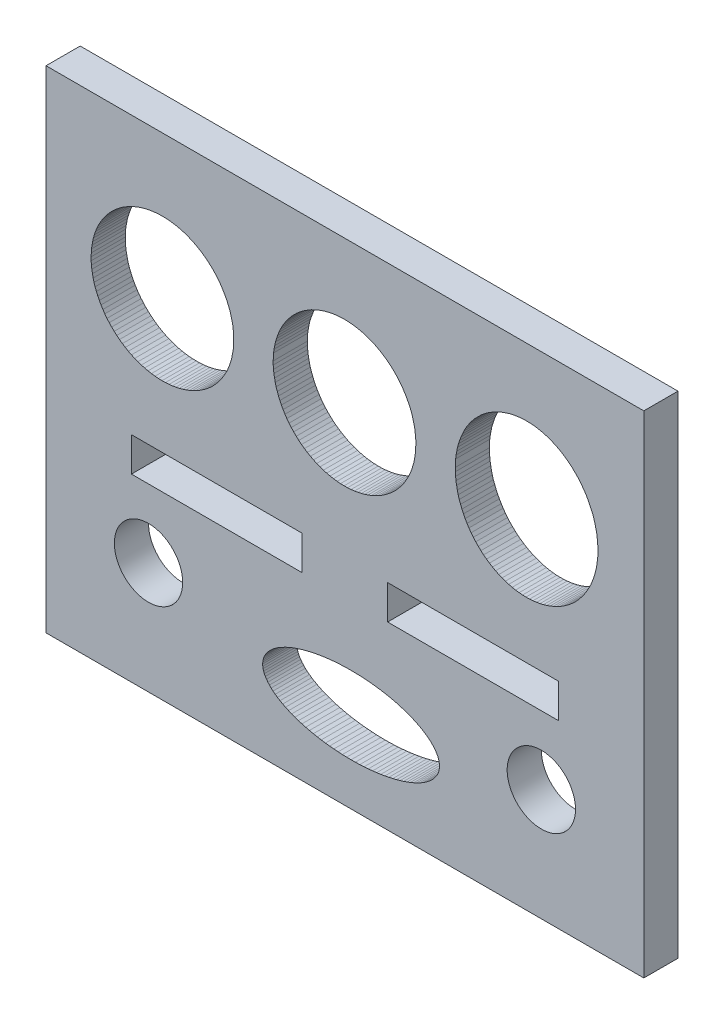
SolidWorks part; units mm, degrees
ref_plane "前视基准面" through (0, 0, 0) normal (0, 0, 1) x (1, 0, 0)
ref_plane "上视基准面" through (0, 0, 0) normal (0, 1, 0) x (1, 0, 0)
ref_plane "右视基准面" through (0, 0, 0) normal (1, 0, 0) x (0, 0, -1)
sketch "Model" plane through (0, 0, 0) normal (0, 0, 1) x (1, 0, 0)
  line L0 (794.7597, 604.4916) -> (759.7597, 604.4916)
  line L1 (789.7597, 617.0426) -> (789.7597, 615.0426)
  line L2 (789.7597, 617.0426) -> (779.7597, 617.0426)
  line L3 (779.7597, 615.0426) -> (779.7597, 617.0426)
  line L4 (774.7597, 617.0426) -> (764.7597, 617.0426)
  line L5 (764.7597, 615.0426) -> (764.7597, 617.0426)
  line L6 (789.7597, 615.0426) -> (779.7597, 615.0426)
  line L7 (774.7597, 615.0426) -> (764.7597, 615.0426)
  line L8 (774.7597, 617.0426) -> (774.7597, 615.0426)
  line L9 (794.7597, 633.2493) -> (759.7597, 633.2493)
  line L10 (759.7597, 633.2493) -> (759.7597, 604.4916)
  line L11 (794.7597, 633.2493) -> (794.7597, 604.4916)
  line L12 (787.8604, 620.3577) -> (788.0704, 620.3607)
  line L13 (788.0704, 620.3607) -> (788.2704, 620.3757)
  line L14 (788.2704, 620.3757) -> (788.4804, 620.4017)
  line L15 (788.4804, 620.4017) -> (788.6804, 620.4377)
  line L16 (788.6804, 620.4377) -> (788.8804, 620.4837)
  line L17 (788.8804, 620.4837) -> (789.0804, 620.5417)
  line L18 (789.0804, 620.5417) -> (789.2704, 620.6087)
  line L19 (789.2704, 620.6087) -> (789.4604, 620.6867)
  line L20 (789.4604, 620.6867) -> (789.6504, 620.7737)
  line L21 (789.6504, 620.7737) -> (789.8404, 620.8717)
  line L22 (789.8404, 620.8717) -> (790.0204, 620.9787)
  line L23 (790.0204, 620.9787) -> (790.1904, 621.0947)
  line L24 (790.1904, 621.0947) -> (790.3604, 621.2197)
  line L25 (790.3604, 621.2197) -> (790.5204, 621.3537)
  line L26 (790.5204, 621.3537) -> (790.6804, 621.4957)
  line L27 (790.6804, 621.4957) -> (790.8304, 621.6467)
  line L28 (790.8304, 621.6467) -> (790.9704, 621.8047)
  line L29 (790.9704, 621.8047) -> (791.1004, 621.9697)
  line L30 (791.1004, 621.9697) -> (791.2304, 622.1417)
  line L31 (791.2304, 622.1417) -> (791.3504, 622.3207)
  line L32 (791.3504, 622.3207) -> (791.4604, 622.5057)
  line L33 (791.4604, 622.5057) -> (791.5604, 622.6957)
  line L34 (791.5604, 622.6957) -> (791.6604, 622.8917)
  line L35 (791.6604, 622.8917) -> (791.7404, 623.0917)
  line L36 (791.7404, 623.0917) -> (791.8204, 623.2957)
  line L37 (791.8204, 623.2957) -> (791.8804, 623.5037)
  line L38 (791.8804, 623.5037) -> (791.9404, 623.7147)
  line L39 (791.9404, 623.7147) -> (791.9904, 623.9287)
  line L40 (791.9904, 623.9287) -> (792.0204, 624.1447)
  line L41 (792.0204, 624.1447) -> (792.0504, 624.3627)
  line L42 (792.0504, 624.3627) -> (792.0704, 624.5817)
  line L43 (792.0704, 624.5817) -> (792.0704, 624.8017)
  line L44 (792.0704, 624.8017) -> (792.0704, 625.0207)
  line L45 (792.0704, 625.0207) -> (792.0504, 625.2397)
  line L46 (792.0504, 625.2397) -> (792.0304, 625.4577)
  line L47 (792.0304, 625.4577) -> (792.0004, 625.6747)
  line L48 (792.0004, 625.6747) -> (791.9504, 625.8887)
  line L49 (791.9504, 625.8887) -> (791.9004, 626.1007)
  line L50 (791.9004, 626.1007) -> (791.8404, 626.3097)
  line L51 (791.8404, 626.3097) -> (791.7704, 626.5157)
  line L52 (791.7704, 626.5157) -> (791.6804, 626.7167)
  line L53 (791.6804, 626.7167) -> (791.5904, 626.9137)
  line L54 (791.5904, 626.9137) -> (791.4904, 627.1057)
  line L55 (791.4904, 627.1057) -> (791.3904, 627.2917)
  line L56 (791.3904, 627.2917) -> (791.2704, 627.4717)
  line L57 (791.2704, 627.4717) -> (791.1404, 627.6457)
  line L58 (791.1404, 627.6457) -> (791.0104, 627.8137)
  line L59 (791.0104, 627.8137) -> (790.8704, 627.9737)
  line L60 (790.8704, 627.9737) -> (790.7204, 628.1257)
  line L61 (790.7204, 628.1257) -> (790.5704, 628.2707)
  line L62 (790.5704, 628.2707) -> (790.4104, 628.4067)
  line L63 (790.4104, 628.4067) -> (790.2404, 628.5347)
  line L64 (790.2404, 628.5347) -> (790.0704, 628.6527)
  line L65 (790.0704, 628.6527) -> (789.8904, 628.7627)
  line L66 (789.8904, 628.7627) -> (789.7104, 628.8627)
  line L67 (789.7104, 628.8627) -> (789.5204, 628.9527)
  line L68 (789.5204, 628.9527) -> (789.3304, 629.0327)
  line L69 (789.3304, 629.0327) -> (789.1404, 629.1037)
  line L70 (789.1404, 629.1037) -> (788.9404, 629.1637)
  line L71 (788.9404, 629.1637) -> (788.7404, 629.2127)
  line L72 (788.7404, 629.2127) -> (788.5404, 629.2517)
  line L73 (788.5404, 629.2517) -> (788.3404, 629.2807)
  line L74 (788.3404, 629.2807) -> (788.1304, 629.2977)
  line L75 (788.1304, 629.2977) -> (787.9304, 629.3047)
  line L76 (787.9304, 629.3047) -> (787.7204, 629.3007)
  line L77 (787.7204, 629.3007) -> (787.5204, 629.2857)
  line L78 (787.5204, 629.2857) -> (787.3204, 629.2607)
  line L79 (787.3204, 629.2607) -> (787.1104, 629.2247)
  line L80 (787.1104, 629.2247) -> (786.9104, 629.1777)
  line L81 (786.9104, 629.1777) -> (786.7204, 629.1207)
  line L82 (786.7204, 629.1207) -> (786.5204, 629.0537)
  line L83 (786.5204, 629.0537) -> (786.3304, 628.9757)
  line L84 (786.3304, 628.9757) -> (786.1404, 628.8877)
  line L85 (786.1404, 628.8877) -> (785.9604, 628.7907)
  line L86 (785.9604, 628.7907) -> (785.7804, 628.6837)
  line L87 (785.7804, 628.6837) -> (785.6004, 628.5677)
  line L88 (785.6004, 628.5677) -> (785.4404, 628.4417)
  line L89 (785.4404, 628.4417) -> (785.2704, 628.3077)
  line L90 (785.2704, 628.3077) -> (785.1204, 628.1657)
  line L91 (785.1204, 628.1657) -> (784.9704, 628.0157)
  line L92 (784.9704, 628.0157) -> (784.8204, 627.8577)
  line L93 (784.8204, 627.8577) -> (784.6904, 627.6917)
  line L94 (784.6904, 627.6917) -> (784.5604, 627.5197)
  line L95 (784.5604, 627.5197) -> (784.4404, 627.3407)
  line L96 (784.4404, 627.3407) -> (784.3304, 627.1567)
  line L97 (784.3304, 627.1567) -> (784.2304, 626.9657)
  line L98 (784.2304, 626.9657) -> (784.1404, 626.7707)
  line L99 (784.1404, 626.7707) -> (784.0504, 626.5707)
  line L100 (784.0504, 626.5707) -> (783.9804, 626.3657)
  line L101 (783.9804, 626.3657) -> (783.9104, 626.1577)
  line L102 (783.9104, 626.1577) -> (783.8504, 625.9467)
  line L103 (783.8504, 625.9467) -> (783.8104, 625.7327)
  line L104 (783.8104, 625.7327) -> (783.7704, 625.5167)
  line L105 (783.7704, 625.5167) -> (783.7404, 625.2987)
  line L106 (783.7404, 625.2987) -> (783.7304, 625.0797)
  line L107 (783.7304, 625.0797) -> (783.7204, 624.8607)
  line L108 (783.7204, 624.8607) -> (783.7204, 624.6407)
  line L109 (783.7204, 624.6407) -> (783.7404, 624.4217)
  line L110 (783.7404, 624.4217) -> (783.7604, 624.2037)
  line L111 (783.7604, 624.2037) -> (783.8004, 623.9877)
  line L112 (783.8004, 623.9877) -> (783.8404, 623.7727)
  line L113 (783.8404, 623.7727) -> (783.8904, 623.5607)
  line L114 (783.8904, 623.5607) -> (783.9504, 623.3517)
  line L115 (783.9504, 623.3517) -> (784.0304, 623.1467)
  line L116 (784.0304, 623.1467) -> (784.1104, 622.9447)
  line L117 (784.1104, 622.9447) -> (784.2004, 622.7487)
  line L118 (784.2004, 622.7487) -> (784.3004, 622.5567)
  line L119 (784.3004, 622.5567) -> (784.4104, 622.3707)
  line L120 (784.4104, 622.3707) -> (784.5204, 622.1897)
  line L121 (784.5204, 622.1897) -> (784.6504, 622.0157)
  line L122 (784.6504, 622.0157) -> (784.7804, 621.8487)
  line L123 (784.7804, 621.8487) -> (784.9204, 621.6887)
  line L124 (784.9204, 621.6887) -> (785.0704, 621.5357)
  line L125 (785.0704, 621.5357) -> (785.2204, 621.3917)
  line L126 (785.2204, 621.3917) -> (785.3804, 621.2557)
  line L127 (785.3804, 621.2557) -> (785.5504, 621.1277)
  line L128 (785.5504, 621.1277) -> (785.7204, 621.0087)
  line L129 (785.7204, 621.0087) -> (785.9004, 620.8997)
  line L130 (785.9004, 620.8997) -> (786.0804, 620.7997)
  line L131 (786.0804, 620.7997) -> (786.2704, 620.7087)
  line L132 (786.2704, 620.7087) -> (786.4604, 620.6287)
  line L133 (786.4604, 620.6287) -> (786.6504, 620.5587)
  line L134 (786.6504, 620.5587) -> (786.8504, 620.4987)
  line L135 (786.8504, 620.4987) -> (787.0504, 620.4487)
  line L136 (787.0504, 620.4487) -> (787.2504, 620.4097)
  line L137 (787.2504, 620.4097) -> (787.4604, 620.3817)
  line L138 (787.4604, 620.3817) -> (787.6604, 620.3637)
  line L139 (787.6604, 620.3637) -> (787.8604, 620.3577)
  line L140 (777.2104, 620.6747) -> (777.4104, 620.6777)
  line L141 (777.4104, 620.6777) -> (777.6204, 620.6917)
  line L142 (777.6204, 620.6917) -> (777.8204, 620.7157)
  line L143 (777.8204, 620.7157) -> (778.0204, 620.7497)
  line L144 (778.0204, 620.7497) -> (778.2204, 620.7937)
  line L145 (778.2204, 620.7937) -> (778.4204, 620.8477)
  line L146 (778.4204, 620.8477) -> (778.6104, 620.9117)
  line L147 (778.6104, 620.9117) -> (778.8104, 620.9847)
  line L148 (778.8104, 620.9847) -> (778.9904, 621.0677)
  line L149 (778.9904, 621.0677) -> (779.1804, 621.1597)
  line L150 (779.1804, 621.1597) -> (779.3604, 621.2607)
  line L151 (779.3604, 621.2607) -> (779.5304, 621.3697)
  line L152 (779.5304, 621.3697) -> (779.7004, 621.4887)
  line L153 (779.7004, 621.4887) -> (779.8604, 621.6147)
  line L154 (779.8604, 621.6147) -> (780.0204, 621.7497)
  line L155 (780.0204, 621.7497) -> (780.1704, 621.8907)
  line L156 (780.1704, 621.8907) -> (780.3104, 622.0407)
  line L157 (780.3104, 622.0407) -> (780.4404, 622.1967)
  line L158 (780.4404, 622.1967) -> (780.5704, 622.3587)
  line L159 (780.5704, 622.3587) -> (780.6904, 622.5277)
  line L160 (780.6904, 622.5277) -> (780.8004, 622.7027)
  line L161 (780.8004, 622.7027) -> (780.9004, 622.8817)
  line L162 (780.9004, 622.8817) -> (781.0004, 623.0667)
  line L163 (781.0004, 623.0667) -> (781.0804, 623.2557)
  line L164 (781.0804, 623.2557) -> (781.1604, 623.4487)
  line L165 (781.1604, 623.4487) -> (781.2204, 623.6457)
  line L166 (781.2204, 623.6457) -> (781.2804, 623.8447)
  line L167 (781.2804, 623.8447) -> (781.3304, 624.0467)
  line L168 (781.3304, 624.0467) -> (781.3604, 624.2507)
  line L169 (781.3604, 624.2507) -> (781.3904, 624.4567)
  line L170 (781.3904, 624.4567) -> (781.4004, 624.6637)
  line L171 (781.4004, 624.6637) -> (781.4104, 624.8707)
  line L172 (781.4104, 624.8707) -> (781.4104, 625.0777)
  line L173 (781.4104, 625.0777) -> (781.3904, 625.2847)
  line L174 (781.3904, 625.2847) -> (781.3704, 625.4907)
  line L175 (781.3704, 625.4907) -> (781.3404, 625.6957)
  line L176 (781.3404, 625.6957) -> (781.2904, 625.8987)
  line L177 (781.2904, 625.8987) -> (781.2404, 626.0987)
  line L178 (781.2404, 626.0987) -> (781.1804, 626.2957)
  line L179 (781.1804, 626.2957) -> (781.1104, 626.4907)
  line L180 (781.1104, 626.4907) -> (781.0204, 626.6807)
  line L181 (781.0204, 626.6807) -> (780.9304, 626.8667)
  line L182 (780.9304, 626.8667) -> (780.8304, 627.0477)
  line L183 (780.8304, 627.0477) -> (780.7204, 627.2237)
  line L184 (780.7204, 627.2237) -> (780.6104, 627.3937)
  line L185 (780.6104, 627.3937) -> (780.4804, 627.5587)
  line L186 (780.4804, 627.5587) -> (780.3504, 627.7167)
  line L187 (780.3504, 627.7167) -> (780.2104, 627.8677)
  line L188 (780.2104, 627.8677) -> (780.0604, 628.0117)
  line L189 (780.0604, 628.0117) -> (779.9104, 628.1487)
  line L190 (779.9104, 628.1487) -> (779.7504, 628.2767)
  line L191 (779.7504, 628.2767) -> (779.5804, 628.3977)
  line L192 (779.5804, 628.3977) -> (779.4104, 628.5097)
  line L193 (779.4104, 628.5097) -> (779.2304, 628.6137)
  line L194 (779.2304, 628.6137) -> (779.0504, 628.7077)
  line L195 (779.0504, 628.7077) -> (778.8604, 628.7937)
  line L196 (778.8604, 628.7937) -> (778.6704, 628.8697)
  line L197 (778.6704, 628.8697) -> (778.4804, 628.9357)
  line L198 (778.4804, 628.9357) -> (778.2804, 628.9927)
  line L199 (778.2804, 628.9927) -> (778.0804, 629.0397)
  line L200 (778.0804, 629.0397) -> (777.8804, 629.0767)
  line L201 (777.8804, 629.0767) -> (777.6804, 629.1037)
  line L202 (777.6804, 629.1037) -> (777.4704, 629.1197)
  line L203 (777.4704, 629.1197) -> (777.2704, 629.1267)
  line L204 (777.2704, 629.1267) -> (777.0604, 629.1227)
  line L205 (777.0604, 629.1227) -> (776.8604, 629.1087)
  line L206 (776.8604, 629.1087) -> (776.6504, 629.0847)
  line L207 (776.6504, 629.0847) -> (776.4504, 629.0507)
  line L208 (776.4504, 629.0507) -> (776.2504, 629.0067)
  line L209 (776.2504, 629.0067) -> (776.0504, 628.9527)
  line L210 (776.0504, 628.9527) -> (775.8604, 628.8897)
  line L211 (775.8604, 628.8897) -> (775.6704, 628.8157)
  line L212 (775.6704, 628.8157) -> (775.4804, 628.7337)
  line L213 (775.4804, 628.7337) -> (775.2904, 628.6417)
  line L214 (775.2904, 628.6417) -> (775.1204, 628.5407)
  line L215 (775.1204, 628.5407) -> (774.9404, 628.4307)
  line L216 (774.9404, 628.4307) -> (774.7704, 628.3127)
  line L217 (774.7704, 628.3127) -> (774.6104, 628.1857)
  line L218 (774.6104, 628.1857) -> (774.4504, 628.0517)
  line L219 (774.4504, 628.0517) -> (774.3104, 627.9097)
  line L220 (774.3104, 627.9097) -> (774.1604, 627.7607)
  line L221 (774.1604, 627.7607) -> (774.0304, 627.6047)
  line L222 (774.0304, 627.6047) -> (773.9004, 627.4417)
  line L223 (773.9004, 627.4417) -> (773.7804, 627.2727)
  line L224 (773.7804, 627.2727) -> (773.6704, 627.0987)
  line L225 (773.6704, 627.0987) -> (773.5704, 626.9187)
  line L226 (773.5704, 626.9187) -> (773.4704, 626.7347)
  line L227 (773.4704, 626.7347) -> (773.3904, 626.5447)
  line L228 (773.3904, 626.5447) -> (773.3204, 626.3517)
  line L229 (773.3204, 626.3517) -> (773.2504, 626.1557)
  line L230 (773.2504, 626.1557) -> (773.1904, 625.9557)
  line L231 (773.1904, 625.9557) -> (773.1504, 625.7537)
  line L232 (773.1504, 625.7537) -> (773.1104, 625.5497)
  line L233 (773.1104, 625.5497) -> (773.0804, 625.3447)
  line L234 (773.0804, 625.3447) -> (773.0704, 625.1377)
  line L235 (773.0704, 625.1377) -> (773.0604, 624.9307)
  line L236 (773.0604, 624.9307) -> (773.0604, 624.7227)
  line L237 (773.0604, 624.7227) -> (773.0804, 624.5157)
  line L238 (773.0804, 624.5157) -> (773.1004, 624.3097)
  line L239 (773.1004, 624.3097) -> (773.1404, 624.1047)
  line L240 (773.1404, 624.1047) -> (773.1804, 623.9027)
  line L241 (773.1804, 623.9027) -> (773.2304, 623.7017)
  line L242 (773.2304, 623.7017) -> (773.3004, 623.5047)
  line L243 (773.3004, 623.5047) -> (773.3704, 623.3107)
  line L244 (773.3704, 623.3107) -> (773.4504, 623.1207)
  line L245 (773.4504, 623.1207) -> (773.5404, 622.9347)
  line L246 (773.5404, 622.9347) -> (773.6404, 622.7537)
  line L247 (773.6404, 622.7537) -> (773.7504, 622.5777)
  line L248 (773.7504, 622.5777) -> (773.8604, 622.4067)
  line L249 (773.8604, 622.4067) -> (773.9904, 622.2427)
  line L250 (773.9904, 622.2427) -> (774.1204, 622.0847)
  line L251 (774.1204, 622.0847) -> (774.2604, 621.9337)
  line L252 (774.2604, 621.9337) -> (774.4104, 621.7887)
  line L253 (774.4104, 621.7887) -> (774.5604, 621.6527)
  line L254 (774.5604, 621.6527) -> (774.7204, 621.5237)
  line L255 (774.7204, 621.5237) -> (774.8904, 621.4027)
  line L256 (774.8904, 621.4027) -> (775.0604, 621.2907)
  line L257 (775.0604, 621.2907) -> (775.2404, 621.1877)
  line L258 (775.2404, 621.1877) -> (775.4204, 621.0927)
  line L259 (775.4204, 621.0927) -> (775.6104, 621.0077)
  line L260 (775.6104, 621.0077) -> (775.8004, 620.9317)
  line L261 (775.8004, 620.9317) -> (776.0004, 620.8647)
  line L262 (776.0004, 620.8647) -> (776.1904, 620.8087)
  line L263 (776.1904, 620.8087) -> (776.3904, 620.7617)
  line L264 (776.3904, 620.7617) -> (776.5904, 620.7247)
  line L265 (776.5904, 620.7247) -> (776.8004, 620.6977)
  line L266 (776.8004, 620.6977) -> (777.0004, 620.6807)
  line L267 (777.0004, 620.6807) -> (777.2104, 620.6747)
  line L268 (766.5504, 620.6767) -> (766.7504, 620.6797)
  line L269 (766.7504, 620.6797) -> (766.9604, 620.6937)
  line L270 (766.9604, 620.6937) -> (767.1604, 620.7177)
  line L271 (767.1604, 620.7177) -> (767.3604, 620.7507)
  line L272 (767.3604, 620.7507) -> (767.5604, 620.7947)
  line L273 (767.5604, 620.7947) -> (767.7604, 620.8477)
  line L274 (767.7604, 620.8477) -> (767.9504, 620.9107)
  line L275 (767.9504, 620.9107) -> (768.1504, 620.9827)
  line L276 (768.1504, 620.9827) -> (768.3304, 621.0647)
  line L277 (768.3304, 621.0647) -> (768.5204, 621.1557)
  line L278 (768.5204, 621.1557) -> (768.7004, 621.2557)
  line L279 (768.7004, 621.2557) -> (768.8704, 621.3637)
  line L280 (768.8704, 621.3637) -> (769.0404, 621.4807)
  line L281 (769.0404, 621.4807) -> (769.2004, 621.6057)
  line L282 (769.2004, 621.6057) -> (769.3604, 621.7377)
  line L283 (769.3604, 621.7377) -> (769.5104, 621.8787)
  line L284 (769.5104, 621.8787) -> (769.6504, 622.0257)
  line L285 (769.6504, 622.0257) -> (769.7804, 622.1797)
  line L286 (769.7804, 622.1797) -> (769.9104, 622.3407)
  line L287 (769.9104, 622.3407) -> (770.0304, 622.5077)
  line L288 (770.0304, 622.5077) -> (770.1404, 622.6797)
  line L289 (770.1404, 622.6797) -> (770.2404, 622.8577)
  line L290 (770.2404, 622.8577) -> (770.3404, 623.0397)
  line L291 (770.3404, 623.0397) -> (770.4204, 623.2267)
  line L292 (770.4204, 623.2267) -> (770.5004, 623.4167)
  line L293 (770.5004, 623.4167) -> (770.5604, 623.6107)
  line L294 (770.5604, 623.6107) -> (770.6204, 623.8087)
  line L295 (770.6204, 623.8087) -> (770.6604, 624.0077)
  line L296 (770.6604, 624.0077) -> (770.7004, 624.2097)
  line L297 (770.7004, 624.2097) -> (770.7304, 624.4127)
  line L298 (770.7304, 624.4127) -> (770.7404, 624.6167)
  line L299 (770.7404, 624.6167) -> (770.7504, 624.8217)
  line L300 (770.7504, 624.8217) -> (770.7504, 625.0267)
  line L301 (770.7504, 625.0267) -> (770.7304, 625.2317)
  line L302 (770.7304, 625.2317) -> (770.7104, 625.4347)
  line L303 (770.7104, 625.4347) -> (770.6804, 625.6367)
  line L304 (770.6804, 625.6367) -> (770.6304, 625.8377)
  line L305 (770.6304, 625.8377) -> (770.5804, 626.0347)
  line L306 (770.5804, 626.0347) -> (770.5204, 626.2297)
  line L307 (770.5204, 626.2297) -> (770.4404, 626.4217)
  line L308 (770.4404, 626.4217) -> (770.3604, 626.6097)
  line L309 (770.3604, 626.6097) -> (770.2704, 626.7937)
  line L310 (770.2704, 626.7937) -> (770.1704, 626.9727)
  line L311 (770.1704, 626.9727) -> (770.0604, 627.1467)
  line L312 (770.0604, 627.1467) -> (769.9504, 627.3147)
  line L313 (769.9504, 627.3147) -> (769.8204, 627.4777)
  line L314 (769.8204, 627.4777) -> (769.6904, 627.6337)
  line L315 (769.6904, 627.6337) -> (769.5504, 627.7827)
  line L316 (769.5504, 627.7827) -> (769.4004, 627.9247)
  line L317 (769.4004, 627.9247) -> (769.2504, 628.0597)
  line L318 (769.2504, 628.0597) -> (769.0904, 628.1877)
  line L319 (769.0904, 628.1877) -> (768.9204, 628.3067)
  line L320 (768.9204, 628.3067) -> (768.7504, 628.4177)
  line L321 (768.7504, 628.4177) -> (768.5704, 628.5197)
  line L322 (768.5704, 628.5197) -> (768.3904, 628.6127)
  line L323 (768.3904, 628.6127) -> (768.2004, 628.6977)
  line L324 (768.2004, 628.6977) -> (768.0104, 628.7727)
  line L325 (768.0104, 628.7727) -> (767.8204, 628.8387)
  line L326 (767.8204, 628.8387) -> (767.6204, 628.8947)
  line L327 (767.6204, 628.8947) -> (767.4204, 628.9407)
  line L328 (767.4204, 628.9407) -> (767.2204, 628.9767)
  line L329 (767.2204, 628.9767) -> (767.0104, 629.0037)
  line L330 (767.0104, 629.0037) -> (766.8104, 629.0197)
  line L331 (766.8104, 629.0197) -> (766.6104, 629.0267)
  line L332 (766.6104, 629.0267) -> (766.4004, 629.0227)
  line L333 (766.4004, 629.0227) -> (766.2004, 629.0097)
  line L334 (766.2004, 629.0097) -> (765.9904, 628.9857)
  line L335 (765.9904, 628.9857) -> (765.7904, 628.9527)
  line L336 (765.7904, 628.9527) -> (765.5904, 628.9087)
  line L337 (765.5904, 628.9087) -> (765.3904, 628.8557)
  line L338 (765.3904, 628.8557) -> (765.2004, 628.7927)
  line L339 (765.2004, 628.7927) -> (765.0104, 628.7207)
  line L340 (765.0104, 628.7207) -> (764.8204, 628.6387)
  line L341 (764.8204, 628.6387) -> (764.6304, 628.5477)
  line L342 (764.6304, 628.5477) -> (764.4604, 628.4477)
  line L343 (764.4604, 628.4477) -> (764.2804, 628.3397)
  line L344 (764.2804, 628.3397) -> (764.1104, 628.2227)
  line L345 (764.1104, 628.2227) -> (763.9504, 628.0977)
  line L346 (763.9504, 628.0977) -> (763.7904, 627.9647)
  line L347 (763.7904, 627.9647) -> (763.6404, 627.8247)
  line L348 (763.6404, 627.8247) -> (763.5004, 627.6777)
  line L349 (763.5004, 627.6777) -> (763.3704, 627.5237)
  line L350 (763.3704, 627.5237) -> (763.2404, 627.3627)
  line L351 (763.2404, 627.3627) -> (763.1204, 627.1957)
  line L352 (763.1204, 627.1957) -> (763.0104, 627.0237)
  line L353 (763.0104, 627.0237) -> (762.9104, 626.8457)
  line L354 (762.9104, 626.8457) -> (762.8104, 626.6637)
  line L355 (762.8104, 626.6637) -> (762.7304, 626.4767)
  line L356 (762.7304, 626.4767) -> (762.6504, 626.2857)
  line L357 (762.6504, 626.2857) -> (762.5904, 626.0917)
  line L358 (762.5904, 626.0917) -> (762.5304, 625.8947)
  line L359 (762.5304, 625.8947) -> (762.4904, 625.6957)
  line L360 (762.4904, 625.6957) -> (762.4504, 625.4937)
  line L361 (762.4504, 625.4937) -> (762.4204, 625.2907)
  line L362 (762.4204, 625.2907) -> (762.4104, 625.0857)
  line L363 (762.4104, 625.0857) -> (762.4004, 624.8817)
  line L364 (762.4004, 624.8817) -> (762.4004, 624.6767)
  line L365 (762.4004, 624.6767) -> (762.4204, 624.4717)
  line L366 (762.4204, 624.4717) -> (762.4404, 624.2687)
  line L367 (762.4404, 624.2687) -> (762.4804, 624.0667)
  line L368 (762.4804, 624.0667) -> (762.5204, 623.8657)
  line L369 (762.5204, 623.8657) -> (762.5704, 623.6677)
  line L370 (762.5704, 623.6677) -> (762.6304, 623.4727)
  line L371 (762.6304, 623.4727) -> (762.7104, 623.2817)
  line L372 (762.7104, 623.2817) -> (762.7904, 623.0937)
  line L373 (762.7904, 623.0937) -> (762.8804, 622.9097)
  line L374 (762.8804, 622.9097) -> (762.9804, 622.7307)
  line L375 (762.9804, 622.7307) -> (763.0904, 622.5567)
  line L376 (763.0904, 622.5567) -> (763.2004, 622.3887)
  line L377 (763.2004, 622.3887) -> (763.3304, 622.2257)
  line L378 (763.3304, 622.2257) -> (763.4604, 622.0697)
  line L379 (763.4604, 622.0697) -> (763.6004, 621.9207)
  line L380 (763.6004, 621.9207) -> (763.7504, 621.7777)
  line L381 (763.7504, 621.7777) -> (763.9004, 621.6427)
  line L382 (763.9004, 621.6427) -> (764.0604, 621.5157)
  line L383 (764.0604, 621.5157) -> (764.2304, 621.3967)
  line L384 (764.2304, 621.3967) -> (764.4004, 621.2857)
  line L385 (764.4004, 621.2857) -> (764.5804, 621.1837)
  line L386 (764.5804, 621.1837) -> (764.7604, 621.0897)
  line L387 (764.7604, 621.0897) -> (764.9504, 621.0057)
  line L388 (764.9504, 621.0057) -> (765.1404, 620.9307)
  line L389 (765.1404, 620.9307) -> (765.3404, 620.8647)
  line L390 (765.3404, 620.8647) -> (765.5304, 620.8087)
  line L391 (765.5304, 620.8087) -> (765.7304, 620.7627)
  line L392 (765.7304, 620.7627) -> (765.9304, 620.7257)
  line L393 (765.9304, 620.7257) -> (766.1404, 620.6997)
  line L394 (766.1404, 620.6997) -> (766.3404, 620.6827)
  line L395 (766.3404, 620.6827) -> (766.5504, 620.6767)
  line L396 (782.7904, 609.2537) -> (782.7904, 609.3647)
  line L397 (782.7904, 609.3647) -> (782.7704, 609.4757)
  line L398 (782.7704, 609.4757) -> (782.7404, 609.5857)
  line L399 (782.7404, 609.5857) -> (782.7004, 609.6957)
  line L400 (782.7004, 609.6957) -> (782.6404, 609.8037)
  line L401 (782.6404, 609.8037) -> (782.5704, 609.9117)
  line L402 (782.5704, 609.9117) -> (782.4904, 610.0167)
  line L403 (782.4904, 610.0167) -> (782.4004, 610.1207)
  line L404 (782.4004, 610.1207) -> (782.3004, 610.2227)
  line L405 (782.3004, 610.2227) -> (782.1804, 610.3217)
  line L406 (782.1804, 610.3217) -> (782.0604, 610.4187)
  line L407 (782.0604, 610.4187) -> (781.9204, 610.5127)
  line L408 (781.9204, 610.5127) -> (781.7804, 610.6037)
  line L409 (781.7804, 610.6037) -> (781.6204, 610.6907)
  line L410 (781.6204, 610.6907) -> (781.4504, 610.7757)
  line L411 (781.4504, 610.7757) -> (781.2804, 610.8557)
  line L412 (781.2804, 610.8557) -> (781.0904, 610.9327)
  line L413 (781.0904, 610.9327) -> (780.9004, 611.0057)
  line L414 (780.9004, 611.0057) -> (780.7004, 611.0737)
  line L415 (780.7004, 611.0737) -> (780.4904, 611.1377)
  line L416 (780.4904, 611.1377) -> (780.2804, 611.1977)
  line L417 (780.2804, 611.1977) -> (780.0604, 611.2517)
  line L418 (780.0604, 611.2517) -> (779.8304, 611.3017)
  line L419 (779.8304, 611.3017) -> (779.6004, 611.3477)
  line L420 (779.6004, 611.3477) -> (779.3604, 611.3877)
  line L421 (779.3604, 611.3877) -> (779.1204, 611.4217)
  line L422 (779.1204, 611.4217) -> (778.8804, 611.4517)
  line L423 (778.8804, 611.4517) -> (778.6304, 611.4767)
  line L424 (778.6304, 611.4767) -> (778.3804, 611.4957)
  line L425 (778.3804, 611.4957) -> (778.1304, 611.5087)
  line L426 (778.1304, 611.5087) -> (777.8704, 611.5167)
  line L427 (777.8704, 611.5167) -> (777.6204, 611.5197)
  line L428 (777.6204, 611.5197) -> (777.3604, 611.5167)
  line L429 (777.3604, 611.5167) -> (777.1104, 611.5087)
  line L430 (777.1104, 611.5087) -> (776.8604, 611.4957)
  line L431 (776.8604, 611.4957) -> (776.6104, 611.4767)
  line L432 (776.6104, 611.4767) -> (776.3604, 611.4517)
  line L433 (776.3604, 611.4517) -> (776.1204, 611.4217)
  line L434 (776.1204, 611.4217) -> (775.8704, 611.3877)
  line L435 (775.8704, 611.3877) -> (775.6404, 611.3477)
  line L436 (775.6404, 611.3477) -> (775.4104, 611.3017)
  line L437 (775.4104, 611.3017) -> (775.1804, 611.2517)
  line L438 (775.1804, 611.2517) -> (774.9604, 611.1977)
  line L439 (774.9604, 611.1977) -> (774.7404, 611.1377)
  line L440 (774.7404, 611.1377) -> (774.5404, 611.0737)
  line L441 (774.5404, 611.0737) -> (774.3304, 611.0057)
  line L442 (774.3304, 611.0057) -> (774.1404, 610.9327)
  line L443 (774.1404, 610.9327) -> (773.9604, 610.8557)
  line L444 (773.9604, 610.8557) -> (773.7804, 610.7757)
  line L445 (773.7804, 610.7757) -> (773.6204, 610.6907)
  line L446 (773.6204, 610.6907) -> (773.4604, 610.6037)
  line L447 (773.4604, 610.6037) -> (773.3104, 610.5127)
  line L448 (773.3104, 610.5127) -> (773.1804, 610.4187)
  line L449 (773.1804, 610.4187) -> (773.0504, 610.3217)
  line L450 (773.0504, 610.3217) -> (772.9404, 610.2227)
  line L451 (772.9404, 610.2227) -> (772.8404, 610.1207)
  line L452 (772.8404, 610.1207) -> (772.7504, 610.0167)
  line L453 (772.7504, 610.0167) -> (772.6704, 609.9117)
  line L454 (772.6704, 609.9117) -> (772.6004, 609.8037)
  line L455 (772.6004, 609.8037) -> (772.5404, 609.6957)
  line L456 (772.5404, 609.6957) -> (772.5004, 609.5857)
  line L457 (772.5004, 609.5857) -> (772.4704, 609.4757)
  line L458 (772.4704, 609.4757) -> (772.4504, 609.3647)
  line L459 (772.4504, 609.3647) -> (772.4404, 609.2537)
  line L460 (772.4404, 609.2537) -> (772.4504, 609.1417)
  line L461 (772.4504, 609.1417) -> (772.4704, 609.0317)
  line L462 (772.4704, 609.0317) -> (772.5004, 608.9207)
  line L463 (772.5004, 608.9207) -> (772.5404, 608.8117)
  line L464 (772.5404, 608.8117) -> (772.6004, 608.7027)
  line L465 (772.6004, 608.7027) -> (772.6704, 608.5957)
  line L466 (772.6704, 608.5957) -> (772.7504, 608.4897)
  line L467 (772.7504, 608.4897) -> (772.8404, 608.3857)
  line L468 (772.8404, 608.3857) -> (772.9404, 608.2847)
  line L469 (772.9404, 608.2847) -> (773.0504, 608.1847)
  line L470 (773.0504, 608.1847) -> (773.1804, 608.0887)
  line L471 (773.1804, 608.0887) -> (773.3104, 607.9947)
  line L472 (773.3104, 607.9947) -> (773.4604, 607.9037)
  line L473 (773.4604, 607.9037) -> (773.6204, 607.8157)
  line L474 (773.6204, 607.8157) -> (773.7804, 607.7317)
  line L475 (773.7804, 607.7317) -> (773.9604, 607.6507)
  line L476 (773.9604, 607.6507) -> (774.1404, 607.5737)
  line L477 (774.1404, 607.5737) -> (774.3304, 607.5017)
  line L478 (774.3304, 607.5017) -> (774.5404, 607.4327)
  line L479 (774.5404, 607.4327) -> (774.7404, 607.3687)
  line L480 (774.7404, 607.3687) -> (774.9604, 607.3097)
  line L481 (774.9604, 607.3097) -> (775.1804, 607.2547)
  line L482 (775.1804, 607.2547) -> (775.4104, 607.2047)
  line L483 (775.4104, 607.2047) -> (775.6404, 607.1597)
  line L484 (775.6404, 607.1597) -> (775.8704, 607.1197)
  line L485 (775.8704, 607.1197) -> (776.1204, 607.0847)
  line L486 (776.1204, 607.0847) -> (776.3604, 607.0547)
  line L487 (776.3604, 607.0547) -> (776.6104, 607.0307)
  line L488 (776.6104, 607.0307) -> (776.8604, 607.0117)
  line L489 (776.8604, 607.0117) -> (777.1104, 606.9977)
  line L490 (777.1104, 606.9977) -> (777.3604, 606.9897)
  line L491 (777.3604, 606.9897) -> (777.6204, 606.9867)
  line L492 (777.6204, 606.9867) -> (777.8704, 606.9897)
  line L493 (777.8704, 606.9897) -> (778.1304, 606.9977)
  line L494 (778.1304, 606.9977) -> (778.3804, 607.0117)
  line L495 (778.3804, 607.0117) -> (778.6304, 607.0307)
  line L496 (778.6304, 607.0307) -> (778.8804, 607.0547)
  line L497 (778.8804, 607.0547) -> (779.1204, 607.0847)
  line L498 (779.1204, 607.0847) -> (779.3604, 607.1197)
  line L499 (779.3604, 607.1197) -> (779.6004, 607.1597)
  line L500 (779.6004, 607.1597) -> (779.8304, 607.2047)
  line L501 (779.8304, 607.2047) -> (780.0604, 607.2547)
  line L502 (780.0604, 607.2547) -> (780.2804, 607.3097)
  line L503 (780.2804, 607.3097) -> (780.4904, 607.3687)
  line L504 (780.4904, 607.3687) -> (780.7004, 607.4327)
  line L505 (780.7004, 607.4327) -> (780.9004, 607.5017)
  line L506 (780.9004, 607.5017) -> (781.0904, 607.5737)
  line L507 (781.0904, 607.5737) -> (781.2804, 607.6507)
  line L508 (781.2804, 607.6507) -> (781.4504, 607.7317)
  line L509 (781.4504, 607.7317) -> (781.6204, 607.8157)
  line L510 (781.6204, 607.8157) -> (781.7804, 607.9037)
  line L511 (781.7804, 607.9037) -> (781.9204, 607.9947)
  line L512 (781.9204, 607.9947) -> (782.0604, 608.0887)
  line L513 (782.0604, 608.0887) -> (782.1804, 608.1847)
  line L514 (782.1804, 608.1847) -> (782.3004, 608.2847)
  line L515 (782.3004, 608.2847) -> (782.4004, 608.3857)
  line L516 (782.4004, 608.3857) -> (782.4904, 608.4897)
  line L517 (782.4904, 608.4897) -> (782.5704, 608.5957)
  line L518 (782.5704, 608.5957) -> (782.6404, 608.7027)
  line L519 (782.6404, 608.7027) -> (782.7004, 608.8117)
  line L520 (782.7004, 608.8117) -> (782.7404, 608.9207)
  line L521 (782.7404, 608.9207) -> (782.7704, 609.0317)
  line L522 (782.7704, 609.0317) -> (782.7904, 609.1417)
  line L523 (782.7904, 609.1417) -> (782.7904, 609.2537)
  circle A0 centre (765.7597, 611.0435) radius 2
  circle A1 centre (788.7597, 611.0435) radius 2
extrude "凸台-拉伸1" add sketch "Model" along normal blind 2
